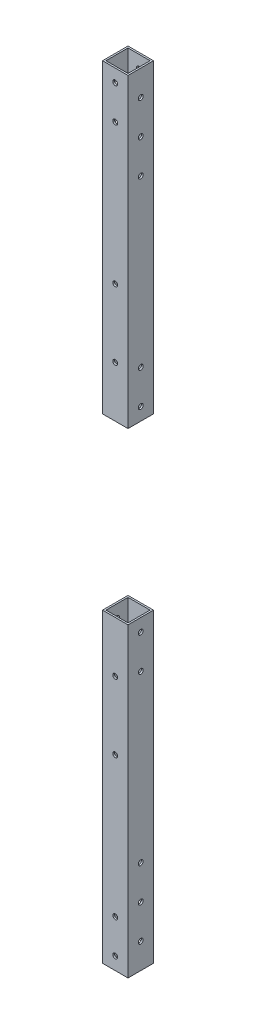
SolidWorks part; units mm, degrees
material "Thornel Mat VMA"
ref_plane "前视基准面" through (0, 0, 0) normal (0, 0, 1) x (1, 0, 0)
ref_plane "上视基准面" through (0, 0, 0) normal (0, 1, 0) x (1, 0, 0)
ref_plane "右视基准面" through (0, 0, 0) normal (1, 0, 0) x (0, 0, -1)
sketch "草图1" plane through (0, 0, 0) normal (0, 1, 0) x (1, 0, 0)
  line L1 (-7.5, -7.5) -> (7.5, -7.5)
  line L2 (-7.5, -7.5) -> (-7.5, 7.5)
  line L3 (-7.5, 7.5) -> (7.5, 7.5)
  line L4 (7.5, -7.5) -> (7.5, 7.5)
  line L5 (-7.5, -7.5) -> (7.5, 7.5) construction
  line L6 (-7.5, 7.5) -> (7.5, -7.5) construction
  point P0 (0, 0)
  dimension "D1" = 15
  dimension "D2" = 15
extrude "拉伸-薄壁1" add sketch "草图1" along normal blind 460 thin thin type one direction reverse wall 1
sketch "草图2" plane through (0, 0, 7.5) normal (0, 0, 1) x (1, 0, 0)
  line L0 (0, 0) -> (0, 460) construction
  line L1 (-7.5, 460) -> (7.5, 460) construction
  line L2 (-1000, 230) -> (49000, 230) construction
  line L3 (-7.5, 0) -> (7.5, 0) construction
  circle A0 centre (0, 7.5) radius 1.45
  circle A1 centre (0, 27.5) radius 1.45
  circle A2 centre (0, 432.5) radius 1.45
  circle A3 centre (0, 452.5) radius 1.45
  circle A4 centre (0, 310) radius 1.45
  circle A5 centre (0, 350) radius 1.45
  circle A7 centre (0, 110) radius 1.45
  circle A8 centre (0, 150) radius 1.45
  point P8 (0, 230)
  dimension "D1" = 2.9
  dimension "D2" = 7.5
  dimension "D3" = 20
  dimension "D4" = 40
  dimension "D5" = 80
extrude "切除-拉伸1" cut sketch "草图2" against normal through all
sketch "草图3" plane through (7.5, 0, 0) normal (1, 0, 0) x (0, 0, -1)
  line L0 (0, 0) -> (0, 460) construction
  line L1 (-7.5, 460) -> (7.5, 460) construction
  line L2 (-1000, 230) -> (49000, 230) construction
  line L3 (-7.5, 0) -> (7.5, 0) construction
  circle A0 centre (0, 15) radius 1.45
  circle A1 centre (0, 35) radius 1.45
  circle A2 centre (0, 425) radius 1.45
  circle A3 centre (0, 445) radius 1.45
  circle A4 centre (0, 172.5) radius 1.45
  circle A5 centre (0, 192.5) radius 1.45
  circle A6 centre (0, 152.5) radius 1.45
  circle A7 centre (0, 307.5) radius 1.45
  circle A8 centre (0, 267.5) radius 1.45
  circle A9 centre (0, 287.5) radius 1.45
  circle A10 centre (0, 55) radius 1.45
  circle A11 centre (0, 405) radius 1.45
  point P12 (0, 230)
  dimension "D3" = 2.9
  dimension "D4" = 2.9
  dimension "D8" = 20
  dimension "D1" = 15
  dimension "D2" = 20
  dimension "D5" = 20
  dimension "D6" = 20
  dimension "D7" = 115
extrude "切除-拉伸2" cut sketch "草图3" against normal through all
sketch "草图4" plane through (7.5, 0, 0) normal (1, 0, 0) x (0, 0, -1)
  line L0 (-7.5, 460) -> (-7.5, 0) construction
  line L1 (-7.5, 280) -> (7.5, 280)
  line L2 (-7.5, 280) -> (-7.5, 180)
  line L3 (-7.5, 180) -> (7.5, 180)
  line L4 (7.5, 280) -> (7.5, 180)
  line L5 (7.5, 460) -> (7.5, 0) construction
  circle A0 centre (0, 287.5) radius 1.45 construction
  circle A1 centre (0, 172.5) radius 1.45 construction
  dimension "D1" = 7.5
  dimension "D2" = 7.5
extrude "切除-拉伸3" cut sketch "草图4" against normal through all
